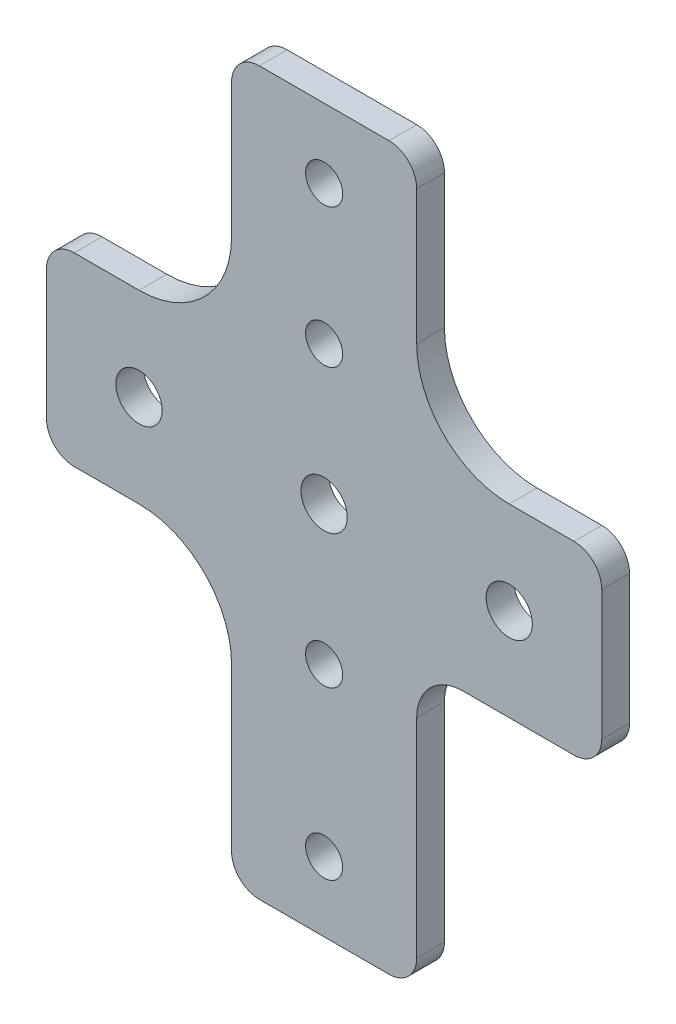
SolidWorks part; units mm, degrees
material "6061 合金"
ref_plane "前视基准面" through (0, 0, 0) normal (0, 0, 1) x (1, 0, 0)
ref_plane "上视基准面" through (0, 0, 0) normal (0, 1, 0) x (1, 0, 0)
ref_plane "右视基准面" through (0, 0, 0) normal (1, 0, 0) x (0, 0, -1)
sketch "草图1" plane through (0, 0, 0) normal (0, 0, 1) x (1, 0, 0)
  line L0 (0, 33.42) -> (0, -26.4859) construction
  line L1 (-40.3702, 0) -> (-4.3903, 0) construction
  line L2 (-30, -10) -> (-30, 10)
  line L3 (-30, 10) -> (-10, 10)
  line L4 (-10, 10) -> (-10, 37.5)
  line L5 (-10, 37.5) -> (10, 37.5)
  line L6 (-10, -37.5) -> (10, -37.5)
  line L7 (-10, -10) -> (-10, -37.5)
  line L8 (-30, -10) -> (-10, -10)
  line L9 (30, -10) -> (10, -10)
  line L10 (10, -10) -> (10, -37.5)
  line L11 (10, 10) -> (10, 37.5)
  line L12 (30, 10) -> (10, 10)
  line L13 (30, -10) -> (30, 10)
  point P5 (30, 0)
  point P16 (-30, 0)
  point P20 (0, -37.5)
  point P21 (0, 37.5)
  dimension "D1" = 75
  dimension "D2" = 60
  dimension "D3" = 20
  dimension "D4" = 20
extrude "凸台-拉伸1" add sketch "草图1" along normal blind 3
sketch "草图3" plane through (0, 0, 3) normal (0, 0, 1) x (1, 0, 0)
  line L0 (10, -37.5) -> (10, -10) construction
  line L1 (10, -40.5) -> (-10, -40.5)
  line L2 (10, -40.5) -> (10, -37.5)
  line L3 (10, -37.5) -> (-10, -37.5)
  line L4 (-10, -40.5) -> (-10, -37.5)
  line L5 (10, -40.5) -> (-10, -37.5) construction
  line L6 (10, -37.5) -> (-10, -40.5) construction
  line L7 (-10, -37.5) -> (10, -37.5) construction
  point P0 (0, -39)
  dimension "D1" = 3
extrude "凸台-拉伸2" add sketch "草图3" against normal up to surface (3 mm away) up to face at (0, 0, 0)
fillet "圆角1" radius 10 3 edges at (-10, 10, 1.5) (-10, -10, 1.5) (10, 10, 1.5)
fillet "圆角2" radius 3 8 edges at (-10, 37.5, 1.5) (30, 10, 1.5) (30, -10, 1.5) (-30, -10, 1.5) (-30, 10, 1.5) (10, 37.5, 1.5) (10, -40.5, 1.5) (-10, -40.5, 1.5)
sketch "草图2" plane through (0, 0, 3) normal (0, 0, 1) x (1, 0, 0)
  line L0 (0, 26.8966) -> (0, -27.2966) construction
  line L1 (-15.7314, 10) -> (33.5291, 10) construction
  line L2 (-12.0337, -10) -> (39.3599, -10) construction
  circle A0 centre (0, 30) radius 2
  circle A1 centre (0, 15) radius 2
  circle A2 centre (0, -15) radius 2
  circle A3 centre (0, -33) radius 2
  dimension "D1" = 4
  dimension "D2" = 4
  dimension "D4" = 15
  dimension "D5" = 5
  dimension "D7" = 4
  dimension "D8" = 4
  dimension "D9" = 5
  dimension "D10" = 18
  dimension "D3" = 10
  dimension "D6" = 10
extrude "切除-拉伸1" cut sketch "草图2" against normal through all
sketch "草图4" plane through (0, 0, 3) normal (0, 0, 1) x (1, 0, 0)
  line L0 (0, 40.2508) -> (0, -9.9749) construction
  circle A0 centre (-20, 0) radius 2.5
  circle A1 centre (0, 0) radius 2.5
  circle A2 centre (20, 0) radius 2.5
  dimension "D1" = 5
  dimension "D2" = 5
  dimension "D3" = 40
extrude "切除-拉伸2" cut sketch "草图4" against normal through all
fillet "圆角3" radius 5 1 edges at (10, -10, 1.5)
